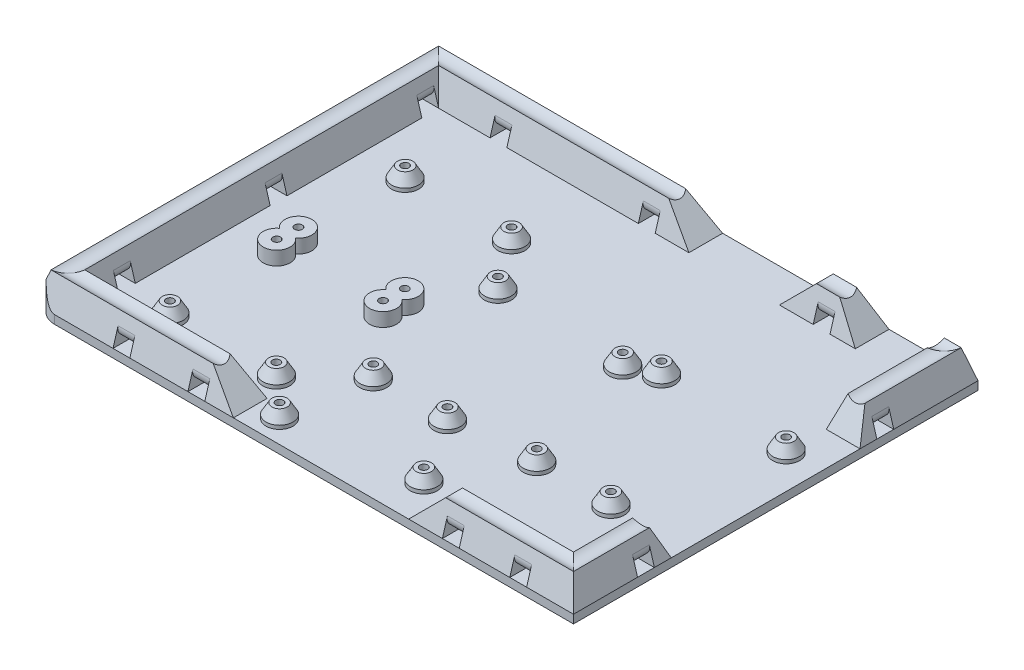
SolidWorks part; units mm, degrees
ref_plane "Front Plane" through (0, 0, 0) normal (0, 0, 1) x (1, 0, 0)
ref_plane "Top Plane" through (0, 0, 0) normal (0, 1, 0) x (1, 0, 0)
ref_plane "Right Plane" through (0, 0, 0) normal (1, 0, 0) x (0, 0, -1)
ref_plane "Plane1" through (0, 39.609, 0) normal (0, -1, 0) x (-1, 0, 0)
sketch "Sketch1" plane through (0, 39.609, 0) normal (0, -1, 0) x (-1, 0, 0)
  line L1 (-120.9006, -136.8501) -> (82.2994, -136.8501)
  line L2 (-120.9006, -136.8501) -> (-120.9006, 15.5499)
  line L3 (-120.9006, 15.5499) -> (82.2994, 15.5499)
  line L4 (82.2994, -136.8501) -> (82.2994, 15.5499)
  line L5 (-3.1716, -133.6751) -> (-37.4616, -133.6751) construction
  line L6 (56.8994, -74.1121) -> (56.8994, -115.8951) construction
  dimension "D1" = 152.4
  dimension "D2" = 3.175
  dimension "D3" = 25.4
  dimension "D4" = 203.2
extrude "Boss-Extrude1" add sketch "Sketch1" against normal blind 3.175
sketch "Sketch2" plane through (0, 42.784, 0) normal (0, 1, 0) x (1, 0, 0)
  line L4 (120.9006, -136.8501) -> (120.9006, 15.5499)
  line L5 (120.9006, 15.5499) -> (-82.2994, 15.5499)
  line L6 (-82.2994, 15.5499) -> (-82.2994, -136.8501)
  line L7 (-82.2994, -136.8501) -> (120.9006, -136.8501)
  line L8 (120.9006, -136.8501) -> (120.9006, 15.5499)
  line L9 (120.9006, 15.5499) -> (-82.2994, 15.5499)
  line L10 (-82.2994, 15.5499) -> (-82.2994, -136.8501)
  line L11 (-82.2994, -136.8501) -> (120.9006, -136.8501)
  circle A4 centre (65.1476, -94.9401) radius 1.5875
  circle A5 centre (60.0676, -42.8701) radius 1.5875
  circle A6 centre (93.0876, -94.9401) radius 1.5875
  circle A7 centre (108.3276, -44.1401) radius 1.5875
  circle A8 centre (49.9076, -47.3151) radius 1.5875 construction
  circle A9 centre (49.9076, -122.2451) radius 1.5875 construction
  circle A10 centre (34.6676, -98.1151) radius 1.5875 construction
  circle A11 centre (6.7276, -98.1151) radius 1.5875 construction
  circle A12 centre (1.6476, -128.3411) radius 1.5875 construction
  circle A13 centre (1.6476, -46.0451) radius 1.5875 construction
  circle A14 centre (49.9076, -47.3151) radius 1.5875
  circle A15 centre (49.9076, -122.2451) radius 1.5875
  circle A16 centre (34.6676, -98.1151) radius 1.5875
  circle A17 centre (6.7276, -98.1151) radius 1.5875
  circle A18 centre (1.6476, -128.3411) radius 1.5875
  circle A19 centre (1.6476, -46.0451) radius 1.5875
  circle A20 centre (-11.9414, -27.3507) radius 1.5 construction
  circle A21 centre (-11.9414, -67.5589) radius 1.5 construction
  circle A22 centre (-12.1192, -75.5853) radius 1.5 construction
  circle A23 centre (-12.1192, -115.7935) radius 1.5 construction
  circle A24 centre (-52.2004, -115.7935) radius 1.5 construction
  circle A25 centre (-52.2004, -75.5853) radius 1.5 construction
  circle A26 centre (-52.0226, -67.5589) radius 1.5 construction
  circle A27 centre (-52.0226, -27.3507) radius 1.5 construction
  circle A28 centre (-11.9414, -27.3507) radius 1.5
  circle A29 centre (-11.9414, -67.5589) radius 1.5
  circle A30 centre (-12.1192, -75.5853) radius 1.5
  circle A31 centre (-12.1192, -115.7935) radius 1.5
  circle A32 centre (-52.2004, -115.7935) radius 1.5
  circle A33 centre (-52.2004, -75.5853) radius 1.5
  circle A34 centre (-52.0226, -67.5589) radius 1.5
  circle A35 centre (-52.0226, -27.3507) radius 1.5
  circle A37 centre (93.0876, -94.9401) radius 1.5875 construction
  circle A39 centre (65.1476, -94.9401) radius 1.5875 construction
  circle A41 centre (60.0676, -42.8701) radius 1.5875 construction
  circle A42 centre (108.3276, -44.1401) radius 1.5875 construction
  dimension "D1" = 0
extrude "Cut-Extrude1" cut sketch "Sketch2" against normal through all contours A4 | A6 | A5 | A7 | A14 | A15 | A16 | A18 | A17 | A31 | A30 | A19 | A29 | A28 | A32 | A33 | A34 | A35
sketch "Sketch3" plane through (0, 42.784, 0) normal (0, 1, 0) x (1, 0, 0)
  circle A0 centre (-52.0226, -27.3507) radius 1.45
  circle A1 centre (-52.0226, -27.3507) radius 5.08
  circle A2 centre (-11.9414, -27.3507) radius 1.45
  circle A3 centre (1.6476, -46.0451) radius 1.45
  circle A4 centre (49.9076, -47.3151) radius 1.45
  circle A5 centre (108.3276, -44.1401) radius 1.45
  circle A6 centre (-11.9414, -67.5589) radius 1.45
  circle A7 centre (-52.0226, -67.5589) radius 1.45
  circle A8 centre (-52.2004, -75.5853) radius 1.45
  circle A9 centre (-12.1192, -75.5853) radius 1.45
  circle A10 centre (6.7276, -98.1151) radius 1.45
  circle A11 centre (34.6676, -98.1151) radius 1.45
  circle A12 centre (-52.2004, -115.7935) radius 1.45
  circle A13 centre (-12.1192, -115.7935) radius 1.45
  circle A14 centre (1.6476, -128.3411) radius 1.45
  circle A15 centre (49.9076, -122.2451) radius 1.45
  circle A16 centre (60.0676, -42.8701) radius 1.45
  circle A17 centre (65.1476, -94.9401) radius 1.45
  circle A18 centre (93.0876, -94.9401) radius 1.45
  circle A19 centre (-11.9414, -27.3507) radius 5.08
  circle A20 centre (1.6476, -46.0451) radius 5.08
  circle A21 centre (49.9076, -47.3151) radius 5.08
  circle A22 centre (108.3276, -44.1401) radius 5.08
  circle A23 centre (93.0876, -94.9401) radius 5.08
  circle A24 centre (65.1476, -94.9401) radius 5.08
  circle A25 centre (60.0676, -42.8701) radius 5.08
  circle A26 centre (-11.9414, -67.5589) radius 5.08
  circle A27 centre (-12.1192, -75.5853) radius 5.08
  circle A28 centre (-52.0226, -67.5589) radius 5.08
  circle A29 centre (-52.2004, -75.5853) radius 5.08
  circle A30 centre (-52.2004, -115.7935) radius 5.08
  circle A31 centre (-12.1192, -115.7935) radius 5.08
  circle A32 centre (6.7276, -98.1151) radius 5.08
  circle A33 centre (34.6676, -98.1151) radius 5.08
  circle A34 centre (49.9076, -122.2451) radius 5.08
  circle A35 centre (1.6476, -128.3411) radius 5.08
  circle M1 centre (-52.0226, -27.3507) radius 1.5
  circle M2 centre (-52.0226, -67.5589) radius 1.5
  circle M3 centre (-52.2004, -75.5853) radius 1.5
  circle M4 centre (-52.2004, -115.7935) radius 1.5
  circle M5 centre (-11.9414, -27.3507) radius 1.5
  circle M6 centre (-11.9414, -67.5589) radius 1.5
  circle M7 centre (1.6476, -46.0451) radius 1.5875
  circle M8 centre (-12.1192, -75.5853) radius 1.5
  circle M9 centre (-12.1192, -115.7935) radius 1.5
  circle M10 centre (6.7276, -98.1151) radius 1.5875
  circle M11 centre (1.6476, -128.3411) radius 1.5875
  circle M12 centre (34.6676, -98.1151) radius 1.5875
  circle M13 centre (49.9076, -122.2451) radius 1.5875
  circle M14 centre (49.9076, -47.3151) radius 1.5875
  circle M15 centre (108.3276, -44.1401) radius 1.5875
  circle M16 centre (60.0676, -42.8701) radius 1.5875
  circle M17 centre (93.0876, -94.9401) radius 1.5875
  circle M18 centre (65.1476, -94.9401) radius 1.5875
  dimension "D1" = 2.9
  dimension "D2" = 10.16
extrude "Boss-Extrude2" add sketch "Sketch3" against normal up to surface and the other way blind 5.1816 contours A0 M1 | A1 M1 | A19 M5 | A2 M5 | A18 M17 | A23 M17 | A17 M18 | A24 M18 | A4 M14 | A21 M14 | A5 M15 | A22 M15 | A16 M16 | A25 M16 | A3 M7 | A20 M7 | A7 M2 | A29 A28 M2 | A8 M3 | A28 A29 M3 | A28 A29 | A6 M6 | A27 A26 M6 | A26 A27 | A9 M8 | A26 A27 M8 | A12 M4 | A30 M4 | A13 M9 | A31 M9 | A10 M10 | A32 M10 | A11 M12 | A33 M12 | A14 M11 | A35 M11 | A15 M13 | A34 M13
chamfer "Chamfer1" distance 3.81 angle 30 14 edges at (60.0676, 47.9656, 94.9401) (88.0076, 47.9656, 94.9401) (54.9876, 47.9656, 42.8701) (103.2476, 47.9656, 44.1401) (44.8276, 47.9656, 47.3151) (44.8276, 47.9656, 122.2451) (29.5876, 47.9656, 98.1151) (-3.4324, 47.9656, 128.3411) (1.6476, 47.9656, 98.1151) (-17.1992, 47.9656, 115.7935) (-57.2804, 47.9656, 115.7935) (-3.4324, 47.9656, 46.0451) (-17.0214, 47.9656, 27.3507) (-57.1026, 47.9656, 27.3507)
sketch "Sketch5" plane through (-82.2994, 0, 0) normal (-1, 0, 0) x (0, 0, 1)
  line L0 (71.5031, 42.784) -> (72.7731, 47.9656)
  line L1 (80.6653, 47.9656) -> (71.5031, 47.9656) construction
  line L2 (72.7731, 47.9656) -> (70.2331, 47.9656)
  line L3 (71.641, 47.9656) -> (62.4789, 47.9656) construction
  line L4 (70.2331, 47.9656) -> (71.5031, 42.784)
  line L6 (71.5031, 42.784) -> (71.5031, 50.1115) construction
  dimension "D1" = 2.54
extrude "Cut-Extrude2" [suppressed] cut sketch "Sketch5" against normal through all
sketch "Sketch6" plane through (0, 0, 136.8501) normal (0, 0, 1) x (1, 0, 0)
  line L0 (-82.2994, 42.784) -> (-79.1244, 53.5548)
  line L1 (-79.1244, 53.5548) -> (-72.7744, 53.5548) construction
  line L2 (-72.7744, 53.5548) -> (-69.5994, 42.784)
  line L3 (-69.5994, 42.784) -> (-82.2994, 42.784)
  line L4 (-75.9494, 42.784) -> (-75.9494, 53.5548) construction
  line L5 (-75.9494, 52.4404) -> (-60.97, 52.4404) construction
  line L6 (-46.2344, 52.4404) -> (-43.4344, 52.4404) construction
  arc A0 (-79.1244, 53.5548) -> (-72.7744, 53.5548) centre (-75.9494, 57.5204) ccw
  dimension "D2" = 5.08
  dimension "D1" = 6.35
  dimension "D3" = 12.7
extrude "Boss-Extrude3" add sketch "Sketch6" against normal up to surface (152.4 mm away) up to face at (19.3006, 41.1965, -15.5499)
sketch "Sketch7" plane through (-82.2994, 0, 0) normal (-1, 0, 0) x (0, 0, 1)
  line L0 (136.8501, 42.784) -> (-15.5499, 42.784) construction
  line L1 (-2.8499, 42.784) -> (3.5001, 42.784)
  line L2 (-2.8499, 42.784) -> (-2.8499, 45.324)
  line L3 (-2.8499, 45.324) -> (3.5001, 45.324)
  line L4 (3.5001, 42.784) -> (3.5001, 45.324)
  line L5 (54.3001, 42.784) -> (54.3001, 45.324)
  line L6 (54.3001, 45.324) -> (60.6501, 45.324)
  line L7 (60.6501, 42.784) -> (60.6501, 45.324)
  line L8 (54.3001, 42.784) -> (60.6501, 42.784)
  line L9 (111.4501, 42.784) -> (111.4501, 45.324)
  line L10 (111.4501, 45.324) -> (117.8001, 45.324)
  line L11 (117.8001, 42.784) -> (117.8001, 45.324)
  line L12 (111.4501, 42.784) -> (117.8001, 42.784)
  dimension "D1" = 2.54
  dimension "D2" = 6.35
  dimension "D3" = 12.7
  dimension "D4" = 3
extrude "Cut-Extrude3" cut sketch "Sketch7" against normal up to next
sketch "Sketch8" plane through (0, 42.784, 0) normal (0, 1, 0) x (1, 0, 0)
  line L0 (-82.2994, 15.5499) -> (-52.0761, 15.5499)
  line L1 (-69.5994, 15.5499) -> (120.9006, 15.5499) construction
  line L2 (-52.0761, 15.5499) -> (-52.0761, -14.6734)
  line L3 (-52.0761, -14.6734) -> (-82.2994, 15.5499)
  line L4 (-82.2994, -136.8501) -> (-66.0944, -136.8501)
  line L5 (120.9006, -136.8501) -> (-69.5994, -136.8501) construction
  line L6 (-66.0944, -136.8501) -> (-66.0944, -120.6451)
  line L7 (-66.0944, -120.6451) -> (-82.2994, -136.8501)
  dimension "D1" = 45
  dimension "D2" = 45
extrude "Cut-Extrude4" cut sketch "Sketch8" along normal through all
ref_plane "Plane2" through (24.6854, 0, 0) normal (-1, 0, 0) x (0, 0, 1)
sketch "Sketch9" plane through (24.6854, 0, 0) normal (-1, 0, 0) x (0, 0, 1)
  line L0 (-15.5499, 42.784) -> (-2.8499, 42.784) construction
  line L1 (-2.8499, 42.784) -> (-6.0249, 53.5548) construction
  line L2 (-12.3749, 53.5548) -> (-15.5499, 42.784) construction
  line L3 (-15.5499, 42.784) -> (-2.8499, 42.784)
  line L4 (-2.8499, 42.784) -> (-6.0249, 53.5548)
  line L5 (-12.3749, 53.5548) -> (-15.5499, 42.784)
  arc A0 (-12.3749, 53.5548) -> (-6.0249, 53.5548) centre (-9.1999, 57.5204) ccw construction
  arc A1 (-12.3749, 53.5548) -> (-6.0249, 53.5548) centre (-9.1999, 57.5204) ccw
extrude "Boss-Extrude4" add sketch "Sketch9" along normal up to surface (97.4598 mm away)
sketch "Sketch10" plane through (0, 0, -15.5499) normal (0, 0, -1) x (-1, 0, 0)
  line L0 (-24.6854, 42.784) -> (-24.6854, 53.5548)
  line L1 (-24.6854, 53.5548) -> (-13.9145, 53.5548)
  line L2 (79.1244, 53.5548) -> (-24.6854, 53.5548) construction
  line L3 (-13.9145, 53.5548) -> (-24.6854, 42.784)
  dimension "D1" = 45
extrude "Cut-Extrude5" cut sketch "Sketch10" against normal up to next
sketch "Sketch11" plane through (0, 0, -15.5499) normal (0, 0, -1) x (-1, 0, 0)
  line L0 (82.2994, 42.784) -> (-24.6854, 42.784) construction
  line L1 (-11.9854, 42.784) -> (-5.6354, 42.784)
  line L2 (-11.9854, 42.784) -> (-11.9854, 45.324)
  line L3 (-11.9854, 45.324) -> (-5.6354, 45.324)
  line L4 (-5.6354, 42.784) -> (-5.6354, 45.324)
  line L5 (43.8946, 42.784) -> (43.8946, 45.324)
  line L6 (43.8946, 45.324) -> (50.2446, 45.324)
  line L7 (50.2446, 42.784) -> (50.2446, 45.324)
  line L8 (43.8946, 42.784) -> (50.2446, 42.784)
  dimension "D1" = 2.54
  dimension "D2" = 6.35
  dimension "D3" = 12.7
  dimension "D4" = 2
extrude "Cut-Extrude6" cut sketch "Sketch11" against normal up to next
ref_plane "Plane3" through (-7.2424, 0, 0) normal (1, 0, 0) x (0, 0, -1)
sketch "Sketch12" plane through (-7.2424, 0, 0) normal (1, 0, 0) x (0, 0, -1)
  line L3 (-133.6751, 53.5548) -> (-136.8501, 42.784)
  line L4 (-136.8501, 42.784) -> (-124.1501, 42.784)
  line L5 (-124.1501, 42.784) -> (-127.3251, 53.5548)
  line L6 (-133.6751, 53.5548) -> (-136.8501, 42.784)
  line L7 (-136.8501, 42.784) -> (-124.1501, 42.784)
  line L8 (-124.1501, 42.784) -> (-127.3251, 53.5548)
  arc A1 (-133.6751, 53.5548) -> (-127.3251, 53.5548) centre (-130.5001, 57.5204) ccw
  arc A2 (-133.6751, 53.5548) -> (-127.3251, 53.5548) centre (-130.5001, 57.5204) ccw
  dimension "D1" = 0
extrude "Boss-Extrude5" add sketch "Sketch12" against normal up to surface (75.057 mm away)
sketch "Sketch13" plane through (0, 0, 136.8501) normal (0, 0, 1) x (1, 0, 0)
  line L0 (-7.2424, 42.784) -> (-7.2424, 53.5548)
  line L1 (-7.2424, 53.5548) -> (-18.0133, 53.5548)
  line L2 (-79.1244, 53.5548) -> (-7.2424, 53.5548) construction
  line L3 (-18.0133, 53.5548) -> (-7.2424, 42.784)
  line L4 (-82.2994, 42.784) -> (-7.2424, 42.784) construction
  line L5 (-52.5844, 42.784) -> (-46.2344, 42.784)
  line L6 (-52.5844, 42.784) -> (-52.5844, 45.324)
  line L7 (-52.5844, 45.324) -> (-46.2344, 45.324)
  line L8 (-46.2344, 42.784) -> (-46.2344, 45.324)
  line L10 (-24.3633, 42.784) -> (-18.0133, 42.784)
  line L11 (-24.3633, 42.784) -> (-24.3633, 45.324)
  line L12 (-24.3633, 45.324) -> (-18.0133, 45.324)
  line L13 (-18.0133, 42.784) -> (-18.0133, 45.324)
  line L14 (-46.2344, 55.1404) -> (-46.2344, 52.4404) construction
  dimension "D1" = 45
  dimension "D2" = 2.54
  dimension "D3" = 6.35
extrude "Cut-Extrude7" cut sketch "Sketch13" against normal up to next
ref_plane "Plane6" through (58.7976, 0, 0) normal (1, 0, 0) x (0, 0, -1)
sketch "Sketch14" plane through (58.7976, 0, 0) normal (-1, 0, 0) x (0, 0, 1)
  line L3 (136.8501, 42.784) -> (133.6751, 53.5548)
  line L4 (124.1501, 42.784) -> (136.8501, 42.784)
  line L5 (127.3251, 53.5548) -> (124.1501, 42.784)
  line L6 (136.8501, 42.784) -> (133.6751, 53.5548)
  line L7 (124.1501, 42.784) -> (136.8501, 42.784)
  line L8 (127.3251, 53.5548) -> (124.1501, 42.784)
  arc A1 (127.3251, 53.5548) -> (133.6751, 53.5548) centre (130.5001, 57.5204) ccw
  arc A2 (127.3251, 53.5548) -> (133.6751, 53.5548) centre (130.5001, 57.5204) ccw
  dimension "D1" = 0
extrude "Boss-Extrude6" add sketch "Sketch14" against normal up to surface (62.103 mm away) up to face at (120.9006, 41.1965, 60.6501)
sketch "Sketch15" plane through (0, 42.784, 0) normal (0, 1, 0) x (1, 0, 0)
  line L0 (120.9006, -136.8501) -> (120.9006, -124.1501)
  line L1 (120.9006, -124.1501) -> (108.2006, -124.1501)
  line L2 (120.9006, -124.1501) -> (58.7976, -124.1501) construction
  line L3 (108.2006, -124.1501) -> (120.9006, -136.8501)
  dimension "D1" = 45
extrude "Cut-Extrude8" cut sketch "Sketch15" along normal through all
sketch "Sketch16" plane through (0, 0, 136.8501) normal (0, 0, 1) x (1, 0, 0)
  line L0 (120.9006, 42.784) -> (58.7976, 42.784) construction
  line L1 (71.4976, 42.784) -> (77.8476, 42.784)
  line L2 (71.4976, 42.784) -> (71.4976, 45.324)
  line L3 (71.4976, 45.324) -> (77.8476, 45.324)
  line L4 (77.8476, 42.784) -> (77.8476, 45.324)
  line L5 (58.7976, 42.784) -> (58.7976, 53.5548) construction
  line L6 (96.8976, 42.784) -> (96.8976, 45.324)
  line L7 (96.8976, 45.324) -> (103.2476, 45.324)
  line L8 (103.2476, 42.784) -> (103.2476, 45.324)
  line L9 (96.8976, 42.784) -> (103.2476, 42.784)
  dimension "D1" = 6.35
  dimension "D2" = 2.54
  dimension "D3" = 12.7
  dimension "D5" = 19.05
  dimension "D4" = 2
extrude "Cut-Extrude9" cut sketch "Sketch16" against normal up to next
ref_plane "Plane4" through (0, 0, 60.6501) normal (0, 0, 1) x (1, 0, 0)
mirror "Mirror2" about plane through (0, 0, 60.6501) normal (0, 0, 1) of "Cut-Extrude9", "Cut-Extrude8", "Boss-Extrude6"
sketch "Sketch17" plane through (0, 0, 136.8501) normal (0, 0, 1) x (1, 0, 0)
  line L0 (58.7976, 42.784) -> (58.7976, 53.5548)
  line L1 (58.7976, 53.5548) -> (69.5684, 53.5548)
  line L2 (117.7256, 53.5548) -> (58.7976, 53.5548) construction
  line L3 (69.5684, 53.5548) -> (58.7976, 42.784)
  dimension "D1" = 45
extrude "Cut-Extrude10" cut sketch "Sketch17" against normal up to next
sketch "Sketch18" plane through (0, 0, -15.5499) normal (0, 0, -1) x (-1, 0, 0)
  line L0 (-58.7976, 42.784) -> (-58.7976, 53.5548)
  line L1 (-58.7976, 53.5548) -> (-69.5684, 53.5548)
  line L2 (-69.5684, 53.5548) -> (-58.7976, 42.784)
  dimension "D1" = 45
extrude "Cut-Extrude11" cut sketch "Sketch18" against normal up to next
ref_plane "Plane7" through (0, 0, 100.0201) normal (0, 0, 1) x (1, 0, 0)
sketch "Sketch19" plane through (0, 0, 100.0201) normal (0, 0, 1) x (1, 0, 0)
  line L5 (111.3756, 53.5548) -> (108.2006, 42.784)
  line L6 (120.9006, 42.784) -> (117.7256, 53.5548)
  line L7 (108.2006, 42.784) -> (120.9006, 42.784)
  line L9 (111.3756, 53.5548) -> (108.2006, 42.784)
  line L10 (120.9006, 42.784) -> (117.7256, 53.5548)
  line L11 (108.2006, 42.784) -> (120.9006, 42.784)
  arc A3 (111.3756, 53.5548) -> (117.7256, 53.5548) centre (114.5506, 57.5204) ccw
  arc A5 (111.3756, 53.5548) -> (117.7256, 53.5548) centre (114.5506, 57.5204) ccw
  dimension "D1" = 0
extrude "Boss-Extrude7" add sketch "Sketch19" along normal up to surface (27.305 mm away)
ref_plane "Plane5" through (0, 0, 28.9001) normal (0, 0, -1) x (-1, 0, 0)
sketch "Sketch20" plane through (0, 0, 28.9001) normal (0, 0, -1) x (-1, 0, 0)
  line L5 (-120.9006, 42.784) -> (-108.2006, 42.784)
  line L6 (-117.7256, 53.5548) -> (-120.9006, 42.784)
  line L7 (-108.2006, 42.784) -> (-111.3756, 53.5548)
  line L9 (-120.9006, 42.784) -> (-108.2006, 42.784)
  line L10 (-117.7256, 53.5548) -> (-120.9006, 42.784)
  line L11 (-108.2006, 42.784) -> (-111.3756, 53.5548)
  arc A3 (-117.7256, 53.5548) -> (-111.3756, 53.5548) centre (-114.5506, 57.5204) ccw
  arc A5 (-117.7256, 53.5548) -> (-111.3756, 53.5548) centre (-114.5506, 57.5204) ccw
  dimension "D1" = 0
extrude "Boss-Extrude8" add sketch "Sketch20" along normal up to surface (44.45 mm away)
sketch "Sketch21" plane through (120.9006, 0, 0) normal (1, 0, 0) x (0, 0, -1)
  line L0 (-136.8501, 42.784) -> (-100.0201, 42.784) construction
  line L1 (-112.7201, 42.784) -> (-106.3701, 42.784)
  line L2 (-112.7201, 42.784) -> (-112.7201, 45.324)
  line L3 (-112.7201, 45.324) -> (-106.3701, 45.324)
  line L4 (-106.3701, 42.784) -> (-106.3701, 45.324)
  line L5 (15.5499, 42.784) -> (-28.9001, 42.784) construction
  line L6 (-22.5501, 42.784) -> (-16.2001, 42.784)
  line L7 (-22.5501, 42.784) -> (-22.5501, 45.324)
  line L8 (-22.5501, 45.324) -> (-16.2001, 45.324)
  line L9 (-16.2001, 42.784) -> (-16.2001, 45.324)
  dimension "D1" = 6.35
  dimension "D2" = 2.54
  dimension "D3" = 6.35
  dimension "D4" = 6.35
extrude "Cut-Extrude12" cut sketch "Sketch21" against normal up to next
fillet "Fillet2" radius 3.048 26 edges at (100.0726, 45.324, -3.5986) (74.6726, 45.324, -3.5986) (-81.5507, 45.324, 0.3251) (-81.5507, 45.324, 57.4751) (-81.5507, 45.324, 114.6251) (-21.1883, 45.324, 124.8988) (-49.4094, 45.324, 124.8988) (-70.3482, 45.324, 114.6251) (-70.3482, 45.324, 57.4751) (-70.3482, 45.324, 0.3251) (-47.0696, 45.324, -3.5986) (8.8104, 45.324, -3.5986) (-47.0696, 45.324, -14.8012) (8.8104, 45.324, -14.8012) (74.6726, 45.324, -14.8012) (100.0726, 45.324, -14.8012) (74.6726, 45.324, 124.8988) (100.0726, 45.324, 124.8988) (-49.4094, 45.324, 136.1014) (-21.1883, 45.324, 136.1014) (74.6726, 45.324, 136.1014) (100.0726, 45.324, 136.1014) (120.1518, 45.324, 19.3751) (108.9493, 45.324, 19.3751) (108.9493, 45.324, 109.5451) (120.1518, 45.324, 109.5451)
sketch "Sketch22" plane through (0, 39.609, 0) normal (0, -1, 0) x (1, 0, 0)
  line L0 (-79.1244, 133.6751) -> (-72.7744, 127.3251) construction
  line L1 (117.7256, 133.6751) -> (111.3756, 127.3251) construction
  line L2 (-72.7744, -6.0249) -> (-79.1244, -12.3749) construction
  line L3 (111.3756, -6.0249) -> (117.7256, -12.3749) construction
  circle A0 centre (-75.9494, 130.5001) radius 1.5875
  circle A1 centre (114.5506, 130.5001) radius 1.5875
  circle A2 centre (-75.9494, -9.1999) radius 1.5875
  circle A3 centre (114.5506, -9.1999) radius 1.5875
  dimension "D1" = 3.175
extrude "Cut-Extrude13" cut sketch "Sketch22" against normal blind 12.7
sketch "Sketch23" plane through (120.9006, 0, 0) normal (1, 0, 0) x (0, 0, -1)
  line L0 (-100.0201, 42.784) -> (-100.0201, 53.5548)
  line L1 (-100.0201, 53.5548) -> (-105.0426, 53.5548)
  line L2 (-133.6751, 53.5548) -> (-100.0201, 53.5548) construction
  line L3 (-105.0426, 53.5548) -> (-100.0201, 42.784)
  line L4 (-28.9001, 42.784) -> (-28.9001, 53.5548)
  line L5 (-28.9001, 53.5548) -> (-23.8776, 53.5548)
  line L6 (12.3749, 53.5548) -> (-28.9001, 53.5548) construction
  line L7 (-23.8776, 53.5548) -> (-28.9001, 42.784)
  line L8 (-28.9001, 42.784) -> (-31.9953, 42.7896)
  dimension "D1" = 25
  dimension "D2" = 25
extrude "Cut-Extrude14" cut sketch "Sketch23" against normal up to next contours L1 L3 L0 | L7 L5 L4
sketch "Sketch25" plane through (0, 0, -15.5499) normal (0, 0, -1) x (-1, 0, 0)
  line L0 (-103.2476, 42.784) -> (-87.3726, 42.784)
  line L1 (-96.8976, 42.784) -> (-77.8476, 42.784) construction
  line L2 (-87.3726, 42.784) -> (-78.3348, 53.5548)
  line L3 (-117.7256, 53.5548) -> (-69.5684, 53.5548) construction
  line L4 (-78.3348, 53.5548) -> (-103.2476, 53.5548)
  line L5 (-103.2476, 53.5548) -> (-103.2476, 42.784)
  dimension "D1" = 50
extrude "Cut-Extrude16" cut sketch "Sketch25" against normal up to next
sketch "Sketch26" plane through (103.2476, 0, 0) normal (-1, 0, 0) x (0, 0, 1)
  line L3 (-2.8499, 42.784) -> (-6.0249, 53.5548)
  line L4 (-12.3749, 53.5548) -> (-15.5499, 42.784)
  line L5 (-15.5499, 42.784) -> (-2.8499, 42.784)
  line L6 (-2.8499, 42.784) -> (-6.0249, 53.5548)
  line L7 (-12.3749, 53.5548) -> (-15.5499, 42.784)
  line L8 (-15.5499, 42.784) -> (-2.8499, 42.784)
  arc A1 (-12.3749, 53.5548) -> (-6.0249, 53.5548) centre (-9.1999, 57.5204) ccw
  arc A2 (-12.3749, 53.5548) -> (-6.0249, 53.5548) centre (-9.1999, 57.5204) ccw
  dimension "D1" = 0
extrude "Cut-Extrude17" cut sketch "Sketch26" against normal up to surface (8.128 mm away)
fillet "Fillet3" radius 7.62 2 edges at (-82.2994, 41.1965, 136.8501) (-82.2994, 41.1965, -15.5499)
equation "\"D2@Sketch23\"=\"D1@Sketch23\""
